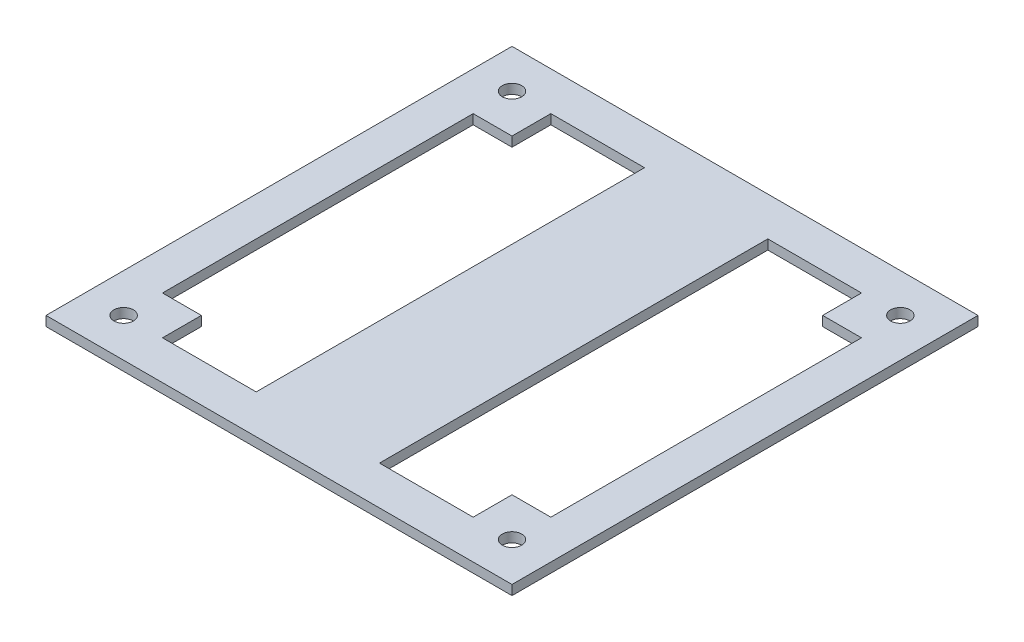
SolidWorks part; units mm, degrees
ref_plane "Front Plane" through (0, 0, 0) normal (0, 0, 1) x (1, 0, 0)
ref_plane "Top Plane" through (0, 0, 0) normal (0, 1, 0) x (1, 0, 0)
ref_plane "Right Plane" through (0, 0, 0) normal (1, 0, 0) x (0, 0, -1)
sketch "Sketch2" plane through (0, 0, 0) normal (0, 1, 0) x (1, 0, 0)
  line L0 (-120, 0) -> (120, 0)
  line L1 (120, 0) -> (120, 240)
  line L2 (120, 240) -> (-120, 240)
  line L3 (-120, 240) -> (-120, 0)
  line L4 (-100, 200) -> (-100, 40)
  line L5 (-80, 20) -> (80, 20)
  line L6 (100, 40) -> (100, 200)
  line L7 (80, 220) -> (-80, 220)
  line L8 (-100, 200) -> (-80, 200)
  line L9 (-80, 200) -> (-80, 220)
  line L10 (80, 220) -> (80, 200)
  line L11 (80, 200) -> (100, 200)
  line L12 (100, 40) -> (80, 40)
  line L13 (80, 40) -> (80, 20)
  line L14 (-100, 40) -> (-80, 40)
  line L15 (-80, 40) -> (-80, 20)
  dimension "D1" = 240
  dimension "D2" = 20
  dimension "D3" = 240
  dimension "D4" = 20
  dimension "D5" = 20
  dimension "D6" = 20
  dimension "D7" = 20
  dimension "D8" = 20
  dimension "D9" = 20
  dimension "D10" = 20
  dimension "D11" = 20
  dimension "D12" = 20
  dimension "D13" = 20
extrude "Boss-Extrude1" add sketch "Sketch2" against normal blind 5
sketch "Sketch3" plane through (0, 0, 0) normal (0, 1, 0) x (1, 0, 0)
  line L0 (-31.75, 220) -> (-31.75, 20)
  line L1 (80, 220) -> (-80, 220) construction
  line L2 (-80, 20) -> (80, 20) construction
  line L3 (-31.75, 220) -> (31.75, 220)
  line L4 (31.75, 220) -> (31.75, 20)
  line L5 (31.75, 20) -> (-31.75, 20)
  point P9 (0, 20)
  dimension "D1" = 63.5
extrude "Boss-Extrude2" add sketch "Sketch3" against normal blind 5
sketch "Sketch8" plane through (0, 0, 0) normal (0, 1, 0) x (1, 0, 0)
  line L0 (0, -61.0884) -> (0, 266.9923) construction
  line L1 (-211.3597, 102.952) -> (217.6689, 102.952) construction
sketch "Sketch10" plane through (0, 0, 0) normal (0, 1, 0) x (1, 0, 0)
  line L0 (-120, 0) -> (120, 0) construction
  line L1 (-120, 240) -> (-120, 0) construction
  line L2 (120, 0) -> (120, 240) construction
  line L3 (120, 240) -> (-120, 240) construction
  line L4 (0, -2.75) -> (0, 2.75) construction
  circle A0 centre (-100, 20) radius 5
  circle A1 centre (100, 20) radius 5
  circle A2 centre (-100, 220) radius 5
  circle A3 centre (100, 220) radius 5
  dimension "D5" = 10
  dimension "D1" = 20
  dimension "D2" = 20
  dimension "D3" = 20
  dimension "D4" = 20
  dimension "D6" = 20
  dimension "D7" = 20
extrude "Cut-Extrude1" cut sketch "Sketch10" against normal blind 10
